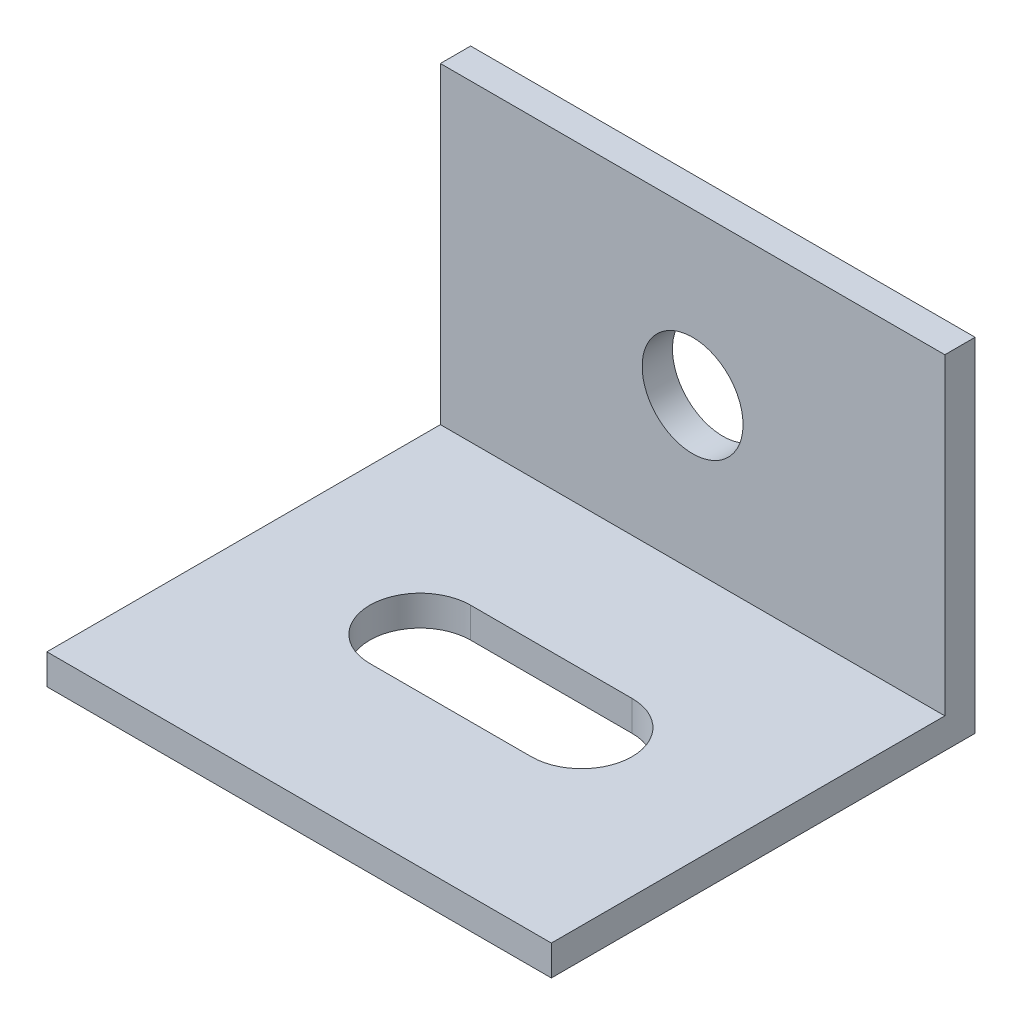
SolidWorks part; units mm, degrees
ref_plane "정면" through (0, 0, 0) normal (0, 0, 1) x (1, 0, 0)
ref_plane "윗면" through (0, 0, 0) normal (0, 1, 0) x (1, 0, 0)
ref_plane "우측면" through (0, 0, 0) normal (1, 0, 0) x (0, 0, -1)
sketch "스케치1" plane through (0, 0, 0) normal (0, 0, 1) x (1, 0, 0)
  line L1 (0, 0) -> (25, 0)
  line L2 (0, 0) -> (0, 17)
  line L3 (0, 17) -> (25, 17)
  line L4 (25, 0) -> (25, 17)
  circle A0 centre (12.5, 9) radius 2.5
  dimension "D3" = 5
  dimension "D4" = 9
  dimension "D1" = 25
  dimension "D2" = 17
  dimension "D5" = 12.5
extrude "보스-돌출1" add sketch "스케치1" along normal blind 1.5
sketch "스케치2" plane through (0, 0, 1.5) normal (0, 0, 1) x (1, 0, 0)
  line L0 (25, 0) -> (25, 17) construction
  line L1 (0, 0) -> (25, 0)
  line L2 (0, 0) -> (0, 1.5)
  line L3 (0, 1.5) -> (25, 1.5)
  line L4 (25, 0) -> (25, 1.5)
  dimension "D1" = 1.5
extrude "보스-돌출2" add sketch "스케치2" along normal blind 19.5
sketch "스케치3" plane through (0, 1.5, 0) normal (0, 1, 0) x (1, 0, 0)
  line L0 (25, -21) -> (0, -21) construction
  line L1 (8.5, -8.5) -> (16.5, -8.5)
  line L2 (8.5, -13.5) -> (16.5, -13.5)
  line L3 (0, -21) -> (0, -1.5) construction
  arc A0 (8.5, -8.5) -> (8.5, -13.5) centre (8.5, -11) ccw
  arc A1 (16.5, -13.5) -> (16.5, -8.5) centre (16.5, -11) ccw
  dimension "D1" = 5
  dimension "D2" = 5
  dimension "D4" = 10
  dimension "D5" = 8.5
  dimension "D3" = 8
extrude "컷-돌출1" cut sketch "스케치3" against normal blind 19.5
